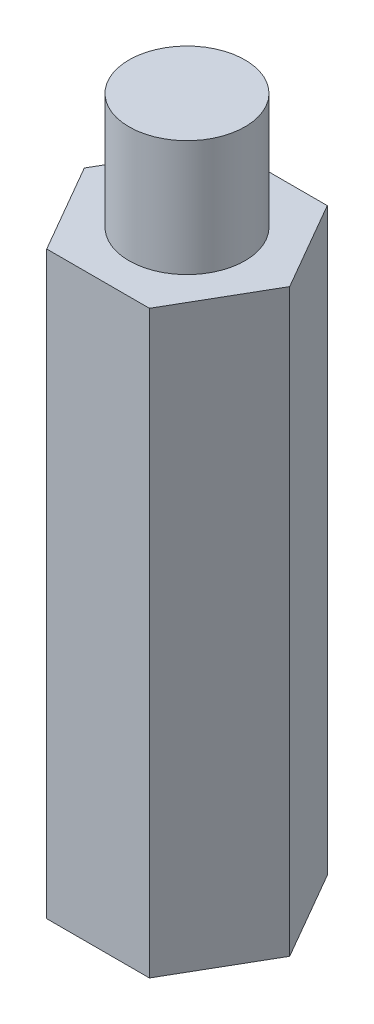
SolidWorks part; units mm, degrees
ref_plane "Front Plane" through (0, 0, 0) normal (0, 0, 1) x (1, 0, 0)
ref_plane "Top Plane" through (0, 0, 0) normal (0, 1, 0) x (1, 0, 0)
ref_plane "Right Plane" through (0, 0, 0) normal (1, 0, 0) x (0, 0, -1)
other "Configuration Table"
sketch "草图1" plane through (0, 0, 0) normal (0, 1, 0) x (1, 0, 0)
  line L1 (2.6558, 0) -> (1.3279, 2.3)
  line L2 (1.3279, 2.3) -> (-1.3279, 2.3)
  line L3 (-1.3279, 2.3) -> (-2.6558, 0)
  line L4 (-2.6558, 0) -> (-1.3279, -2.3)
  line L5 (-1.3279, -2.3) -> (1.3279, -2.3)
  line L6 (1.3279, -2.3) -> (2.6558, 0)
  circle A0 centre (0, 0) radius 2.3 construction
extrude "凸台-拉伸1" add sketch "草图1" along normal blind 15
sketch "草图2" plane through (0, 15, 0) normal (0, 1, 0) x (1, 0, 0)
  circle A0 centre (0, 0) radius 1.5
extrude "凸台-拉伸2" add sketch "草图2" along normal blind 3
sketch "草图3" plane through (0, 0, 0) normal (0, -1, 0) x (1, 0, 0)
  circle A0 centre (0, 0) radius 1.5
  dimension "D1" = 3
extrude "切除-拉伸1" cut sketch "草图3" against normal blind 5
